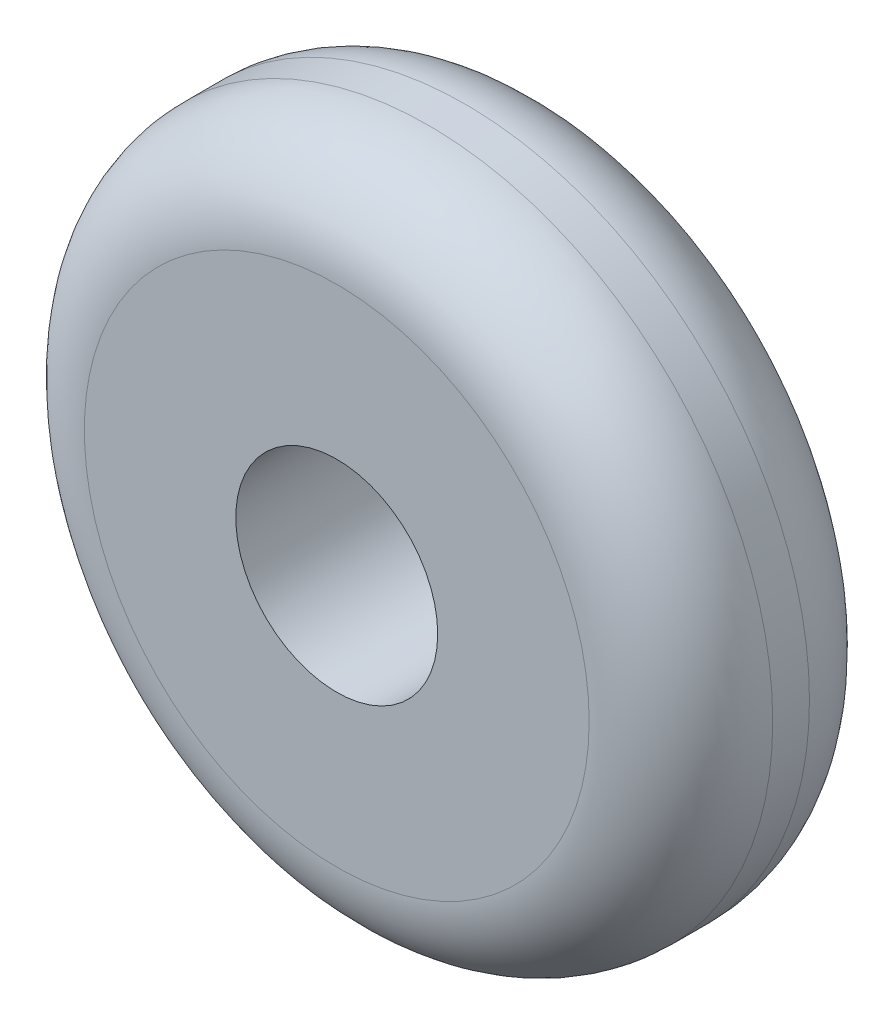
SolidWorks part; units mm, degrees
ref_plane "前视基准面" through (0, 0, 0) normal (0, 0, 1) x (1, 0, 0)
ref_plane "上视基准面" through (0, 0, 0) normal (0, 1, 0) x (1, 0, 0)
ref_plane "右视基准面" through (0, 0, 0) normal (1, 0, 0) x (0, 0, -1)
other "Configuration Table"
sketch "草图1" plane through (0, 0, 0) normal (0, 0, 1) x (1, 0, 0)
  circle A0 centre (0, 0) radius 37.5
  circle A1 centre (0, 0) radius 11
  dimension "D1" = 75
extrude "凸台-拉伸1" add sketch "草图1" along normal blind 24
fillet "圆角1" radius 10 2 edges at (37.5, 0, 0) (37.5, 0, 24)
